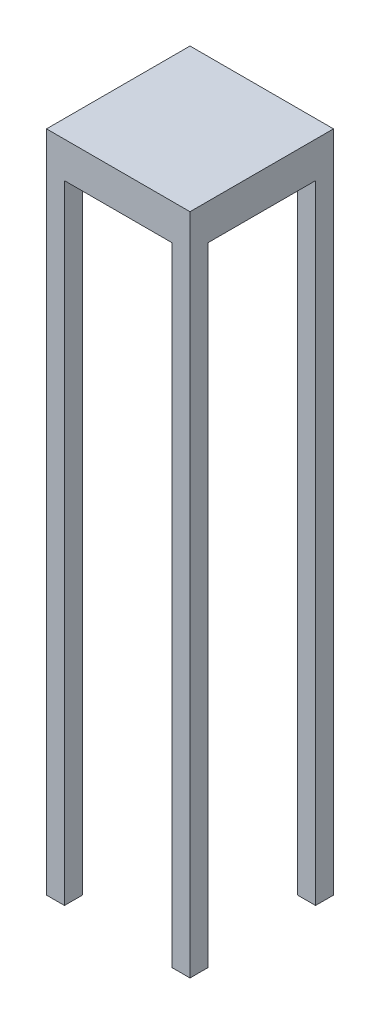
SolidWorks part; units mm, degrees
ref_plane "Alzado" through (0, 0, 0) normal (0, 0, 1) x (1, 0, 0)
ref_plane "Planta" through (0, 0, 0) normal (0, 1, 0) x (1, 0, 0)
ref_plane "Vista lateral" through (0, 0, 0) normal (1, 0, 0) x (0, 0, -1)
sketch "Croquis1" plane through (0, 0, 0) normal (0, 1, 0) x (1, 0, 0)
  line L1 (0, 0) -> (200, 0)
  line L2 (0, 0) -> (0, 200)
  line L3 (0, 200) -> (200, 200)
  line L4 (200, 0) -> (200, 200)
  dimension "D1" = 200
  dimension "D2" = 200
extrude "Saliente-Extruir1" add sketch "Croquis1" along normal blind 50
sketch "Croquis2" plane through (0, 0, 0) normal (0, -1, 0) x (1, 0, 0)
  line L1 (0, 0) -> (25, 0)
  line L2 (0, 0) -> (0, -25)
  line L3 (0, -25) -> (25, -25)
  line L4 (25, 0) -> (25, -25)
  line L5 (200, 0) -> (175, 0)
  line L6 (200, 0) -> (200, -25)
  line L7 (200, -25) -> (175, -25)
  line L8 (175, 0) -> (175, -25)
  line L9 (0, -200) -> (25, -200)
  line L10 (0, -200) -> (0, -175)
  line L11 (0, -175) -> (25, -175)
  line L12 (25, -200) -> (25, -175)
  line L13 (200, -200) -> (175, -200)
  line L14 (200, -200) -> (200, -175)
  line L15 (200, -175) -> (175, -175)
  line L16 (175, -200) -> (175, -175)
extrude "Saliente-Extruir2" add sketch "Croquis2" along normal blind 875
